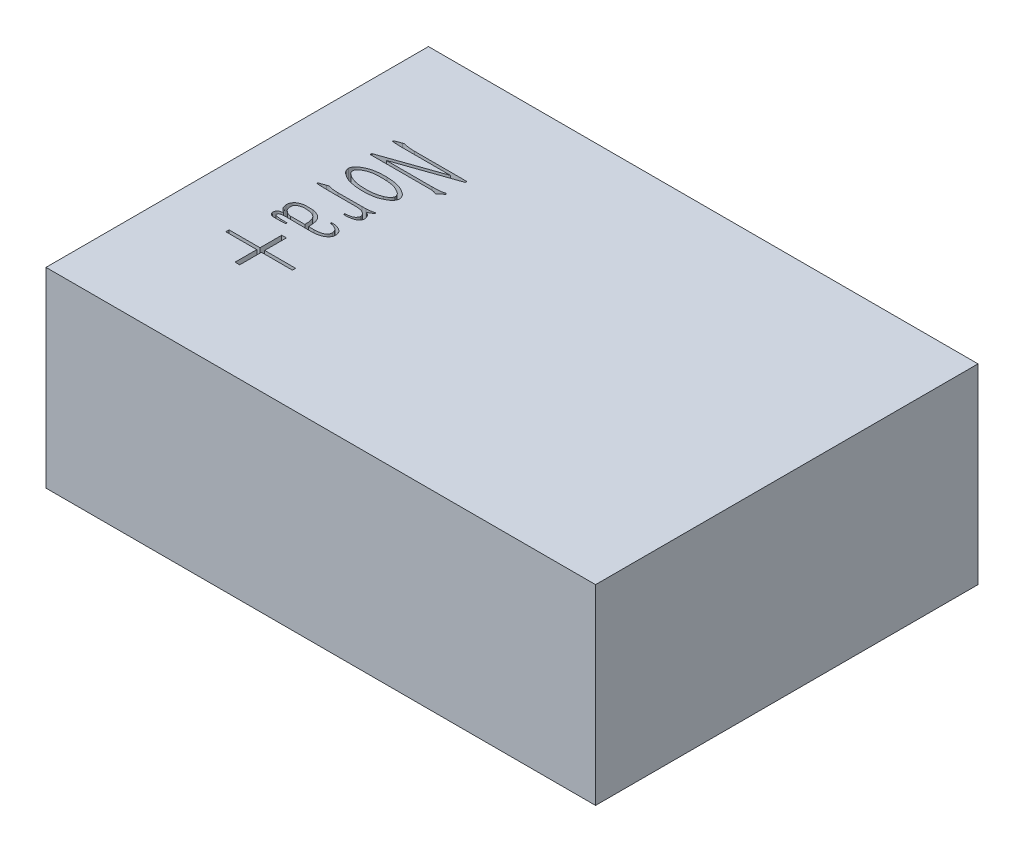
SolidWorks part; units mm, degrees
ref_plane "前视基准面" through (0, 0, 0) normal (0, 0, 1) x (1, 0, 0)
ref_plane "上视基准面" through (0, 0, 0) normal (0, 1, 0) x (1, 0, 0)
ref_plane "右视基准面" through (0, 0, 0) normal (1, 0, 0) x (0, 0, -1)
sketch "草图1" plane through (0, 0, 0) normal (0, 1, 0) x (1, 0, 0)
  line L1 (-33.05, -23) -> (33.05, -23)
  line L2 (-33.05, -23) -> (-33.05, 23)
  line L3 (-33.05, 23) -> (33.05, 23)
  line L4 (33.05, -23) -> (33.05, 23)
  line L5 (-33.05, -23) -> (33.05, 23) construction
  line L6 (-33.05, 23) -> (33.05, -23) construction
  point P0 (0, 0)
  dimension "D1" = 46
  dimension "D2" = 66.1
extrude "凸台-拉伸1" add sketch "草图1" along normal blind 23
sketch "草图2" plane through (0, 23, 0) normal (0, 1, 0) x (1, 0, 0)
  text T0 "\r\n\r\n\r\n\r\nNora+\r\n" font "汉仪长仿宋体" height in points 42
extrude "切除-拉伸1" cut sketch "草图2" against normal blind 2
